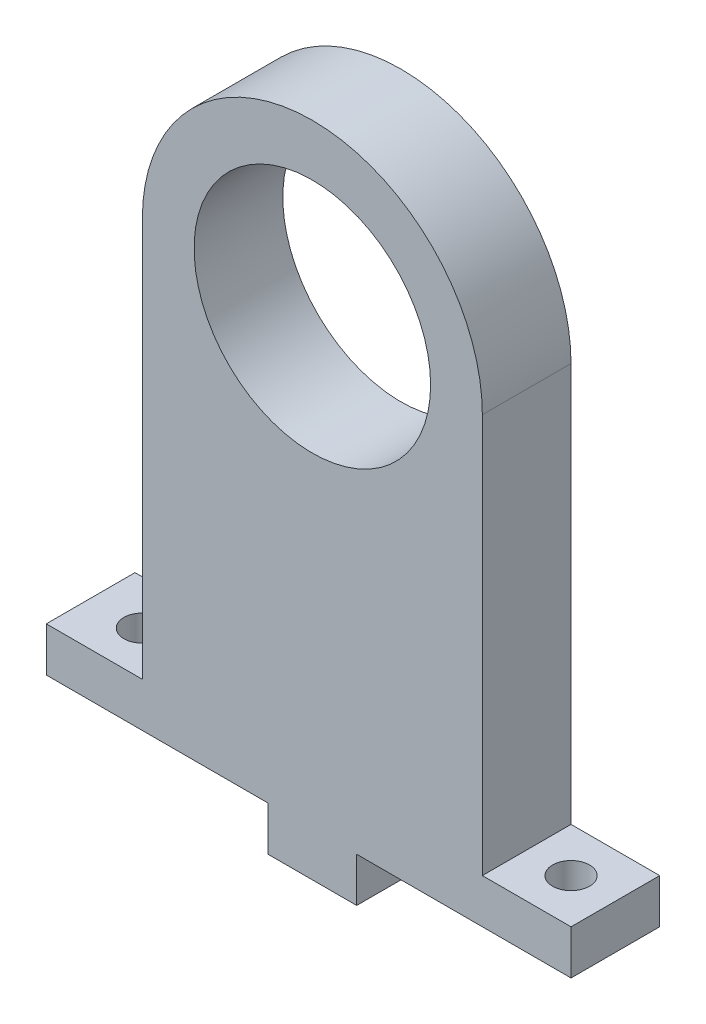
SolidWorks part; units mm, degrees
ref_plane "前视基准面" through (0, 0, 0) normal (0, 0, 1) x (1, 0, 0)
ref_plane "上视基准面" through (0, 0, 0) normal (0, 1, 0) x (1, 0, 0)
ref_plane "右视基准面" through (0, 0, 0) normal (1, 0, 0) x (0, 0, -1)
sketch "草图1" plane through (0, 0, 0) normal (0, 0, 1) x (1, 0, 0)
  line L0 (-3, -30) -> (-18, -30)
  line L1 (11.5, -27) -> (17.5, -27)
  line L2 (-11.5, -27) -> (-18, -27)
  line L3 (-11.5, 0) -> (-11.5, -27)
  line L4 (11.5, 0) -> (11.5, -27)
  line L5 (-18, -27) -> (-18, -30)
  line L6 (17.5, -27) -> (17.5, -30)
  line L7 (17.5, -30) -> (3, -30)
  line L8 (0, -33) -> (-3, -33)
  line L9 (-3, -33) -> (-3, -30)
  line L10 (0, -33) -> (3, -33)
  line L11 (3, -33) -> (3, -30)
  circle A0 centre (0, 0) radius 8
  arc A1 (11.5, 0) -> (-11.5, 0) centre (0, 0) ccw
  dimension "D1" = 3
  dimension "D2" = 16
  dimension "D3" = 11.5
  dimension "D7" = 30
  dimension "D4" = 3
  dimension "D5" = 6
  dimension "D6" = 15
extrude "凸台-拉伸1" add sketch "草图1" along normal blind 6
sketch "草图2" plane through (0, -27, 0) normal (0, 1, 0) x (1, 0, 0)
  circle A0 centre (-14.5, -3) radius 1.25
  circle A1 centre (14.5, -3) radius 1.25
  dimension "D1" = 2.5
  dimension "D2" = 2.5
extrude "切除-拉伸1" cut sketch "草图2" against normal blind 3
